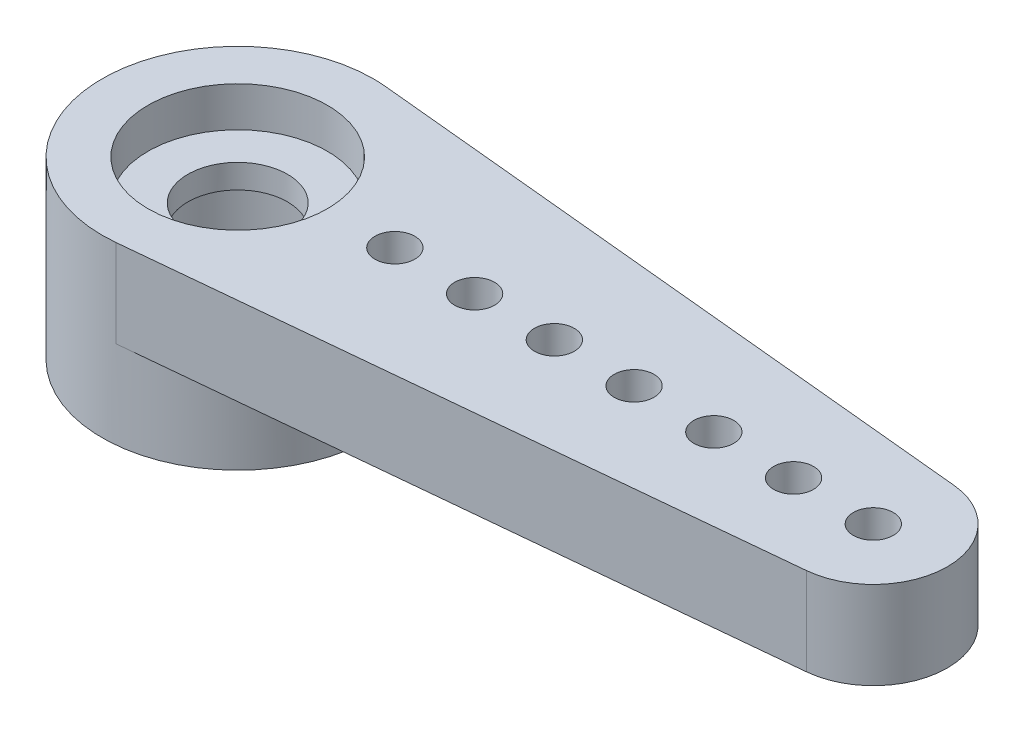
SolidWorks part; units mm, degrees
ref_plane "Plan de face" through (0, 0, 0) normal (0, 0, 1) x (1, 0, 0)
ref_plane "Plan de dessus" through (0, 0, 0) normal (0, 1, 0) x (1, 0, 0)
ref_plane "Plan de droite" through (0, 0, 0) normal (1, 0, 0) x (0, 0, -1)
sketch "Esquisse1" plane through (0, 0, 0) normal (0, 1, 0) x (1, 0, 0)
  line L0 (0, 0) -> (15.9413, 0) construction
  line L1 (0.3287, 3.3841) -> (16.121, 1.85)
  line L2 (0.3287, -3.3841) -> (16.121, -1.85)
  line L3 (0, 3.4) -> (0, -3.4) construction
  arc A0 (0.3287, 3.3841) -> (0.3287, -3.3841) centre (0, 0) ccw
  arc A1 (16.121, 1.85) -> (16.121, -1.85) centre (15.9413, 0) cw
  point P4 (0, 0)
  point P8 (17.8, 0)
  point P9 (-3.4, 0)
  dimension "D1" = 6.8
  dimension "D2" = 3.7
  dimension "D3" = 21.2
extrude "Boss.-Extru.1" add sketch "Esquisse1" along normal blind 2.2
sketch "Esquisse2" plane through (0, 0, 0) normal (0, -1, 0) x (1, 0, 0)
  circle A0 centre (0, 0) radius 3.4
  arc A1 (0.3287, 3.3841) -> (0.3287, -3.3841) centre (0, 0) ccw construction
extrude "Boss.-Extru.2" add sketch "Esquisse2" along normal blind 2.2
sketch "Esquisse3" plane through (0, -2.2, 0) normal (0, -1, 0) x (1, 0, 0)
  circle A0 centre (0, 0) radius 2.1
  dimension "D1" = 4.2
extrude "Enlèv. mat.-Extru.1" cut sketch "Esquisse3" against normal blind 2.8
hole_wizard "Diamètre du perçage Ø2.5 (2.5)1" positions "Esquisse4" profile "Esquisse5" hole size "Ø2.5" standard "DIN" end condition through all
sketch "Esquisse4" plane through (0, 2.2, 0) normal (0, 1, 0) x (1, 0, 0)
  point P0 (0, 0)
sketch "Esquisse5" plane through (0, 2.2, 0) normal (1, 0, 0) x (0, 0, 1)
  line L0 (0, 0) -> (0, 4.4)
  line L1 (0, 4.4) -> (1.25, 4.4)
  line L2 (1.25, 4.4) -> (1.25, 0)
  line L5 (1.25, 0) -> (0, 0)
  line L11 (0, -6.35) -> (0, 107.95) construction
  dimension "Diamètre du perçage jusqu'au prochain" = 2.5
  dimension "Profondeur du perçage jusqu'au prochain" = 4.4
hole_wizard "Diamètre du perçage Ø1.0 (1)1" positions "Esquisse6" profile "Esquisse7" hole size "Ø1.0" standard "DIN" end condition through all
sketch "Esquisse6" plane through (0, 0, 0) normal (0, -1, 0) x (-1, 0, 0)
  point P0 (-15.9413, 0)
  point P7 (-13.9413, 0)
  point P8 (-11.9413, 0)
  point P9 (-9.9413, 0)
  point P10 (-7.9413, 0)
  point P11 (-5.9413, 0)
  point P12 (-3.9413, 0)
  dimension "D1" = 7
sketch "Esquisse7" plane through (15.9413, 0, 0) normal (1, 0, 0) x (0, 0, -1)
  line L0 (0, 0) -> (0, 2.2)
  line L1 (0, 2.2) -> (0.5, 2.2)
  line L2 (0.5, 2.2) -> (0.5, 0)
  line L5 (0.5, 0) -> (0, 0)
  line L11 (0, -6.35) -> (0, 107.95) construction
  dimension "Diamètre du perçage jusqu'au prochain" = 1
  dimension "Profondeur du perçage jusqu'au prochain" = 2.2
sketch "Esquisse8" plane through (0, 2.2, 0) normal (0, 1, 0) x (1, 0, 0)
  circle A0 centre (0, 0) radius 2.25
  dimension "D1" = 4.5
extrude "Enlèv. mat.-Extru.2" cut sketch "Esquisse8" against normal blind 1
